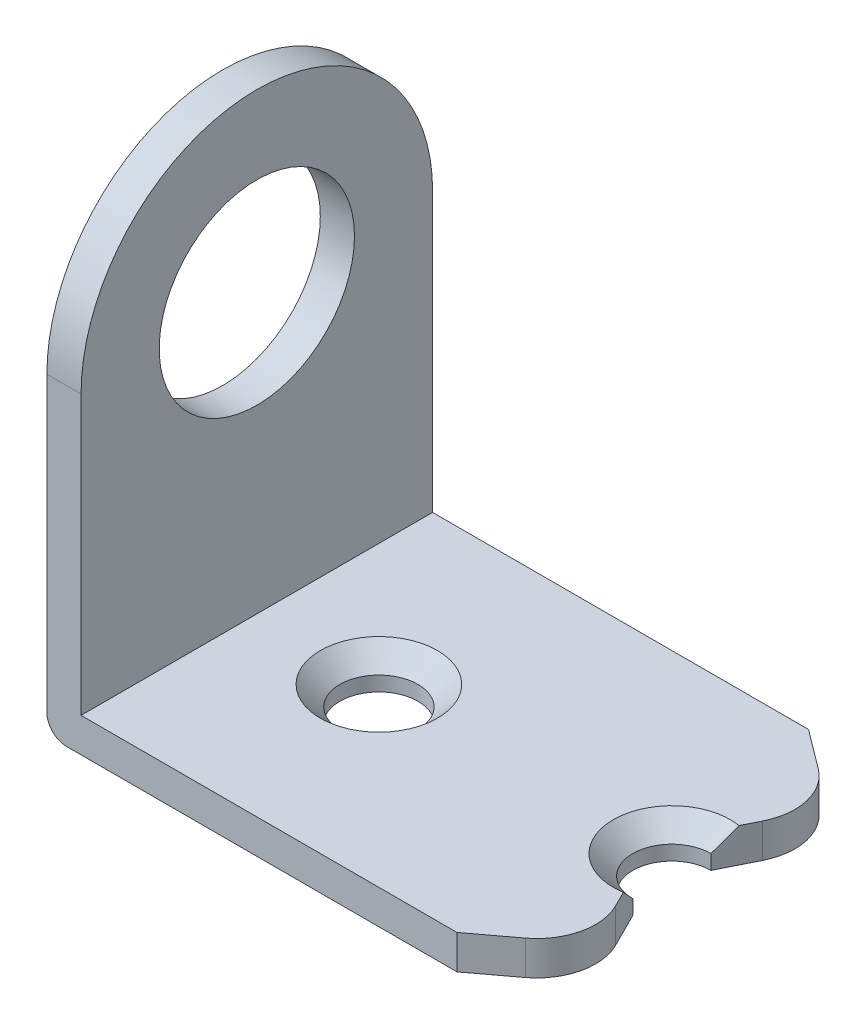
SolidWorks part; units mm, degrees
material "Цинк AG40A (Zn-4Al-0.4Мг; Zamak 3), литье"
ref_plane "Спереди" through (0, 0, 0) normal (0, 0, 1) x (1, 0, 0)
ref_plane "Сверху" through (0, 0, 0) normal (0, 1, 0) x (1, 0, 0)
ref_plane "Справа" through (0, 0, 0) normal (1, 0, 0) x (0, 0, -1)
sketch "Эскиз1" plane through (0, 0, 0) normal (0, 1, 0) x (1, 0, 0)
  line L0 (0, 0) -> (-20.7742, 0) construction
  line L2 (0, -9) -> (28, -9)
  line L3 (0, -9) -> (0, 9)
  line L4 (0, 9) -> (28, 9)
  line L5 (28, -9) -> (28, 9)
  circle A0 centre (8, 0) radius 2
  circle A1 centre (23, 0) radius 2
  point P12 (28, 0)
  dimension "D3" = 4
  dimension "D4" = 4
  dimension "D1" = 28
  dimension "D2" = 18
  dimension "D5" = 5
  dimension "D6" = 20
extrude "Бобышка-Вытянуть1" add sketch "Эскиз1" along normal blind 1.75
sketch "Эскиз2" plane through (0, 0, 0) normal (1, 0, 0) x (0, 0, -1)
  line L0 (-9, 0) -> (-9, 16)
  line L1 (9, 0) -> (9, 16)
  line L2 (9, 0) -> (-9, 0)
  arc A0 (-9, 16) -> (9, 16) centre (0, 16) cw
  circle A1 centre (0, 16) radius 5
  dimension "D1" = 16
  dimension "D2" = 10
extrude "Бобышка-Вытянуть2" add sketch "Эскиз2" along normal blind 1.75
fillet "Скругление1" radius 1 1 edges at (0, 0, 0)
chamfer "Фаска1" distance 1 angle 45 2 edges at (23, 1.75, 2) (8, 1.75, 2)
sketch "Эскиз3" plane through (0, 0, 0) normal (0, -1, 0) x (-1, 0, 0)
  line L0 (-23, 2) -> (-23.8803, 3.7606)
  line L1 (-22.997, 7.5022) -> (-21, 9)
  line L2 (-28, 9) -> (-1, 9) construction
  line L3 (-21, 9) -> (-28, 9)
  line L4 (-28, 9) -> (-28, -9)
  line L5 (-28, -9) -> (-21, -9)
  line L6 (-1, -9) -> (-28, -9) construction
  line L7 (-21, -9) -> (-22.997, -7.5022)
  line L8 (-23.8803, -3.7606) -> (-23, -2)
  line L9 (-28, 0) -> (-6, 0) construction
  circle A0 centre (-23, 0) radius 2 construction
  circle A1 centre (-8, 0) radius 2 construction
  circle A2 centre (-23, 0) radius 2
  arc A3 (-22.997, -7.5022) -> (-23.8803, -3.7606) centre (-21.197, -5.1022) cw
  arc A4 (-23.8803, 3.7606) -> (-22.997, 7.5022) centre (-21.197, 5.1022) cw
  point P29 (-25, 6)
  line M7 (-28, -9) -> (-1, -9)
  line M9 (-1, 9) -> (-28, 9)
  line M10 (-28, 9) -> (-28, -9)
  circle M12 centre (-23, 0) radius 2
  dimension "D4" = 3
  dimension "D1" = 7
  dimension "D2" = 4
  dimension "D3" = 3
extrude "Вырез-Вытянуть1" cut sketch "Эскиз3" against normal up to next contours L9 A2 L0 A4 L1 M10 M9 | L9 L4 L7 A3 L8 M7 M12
